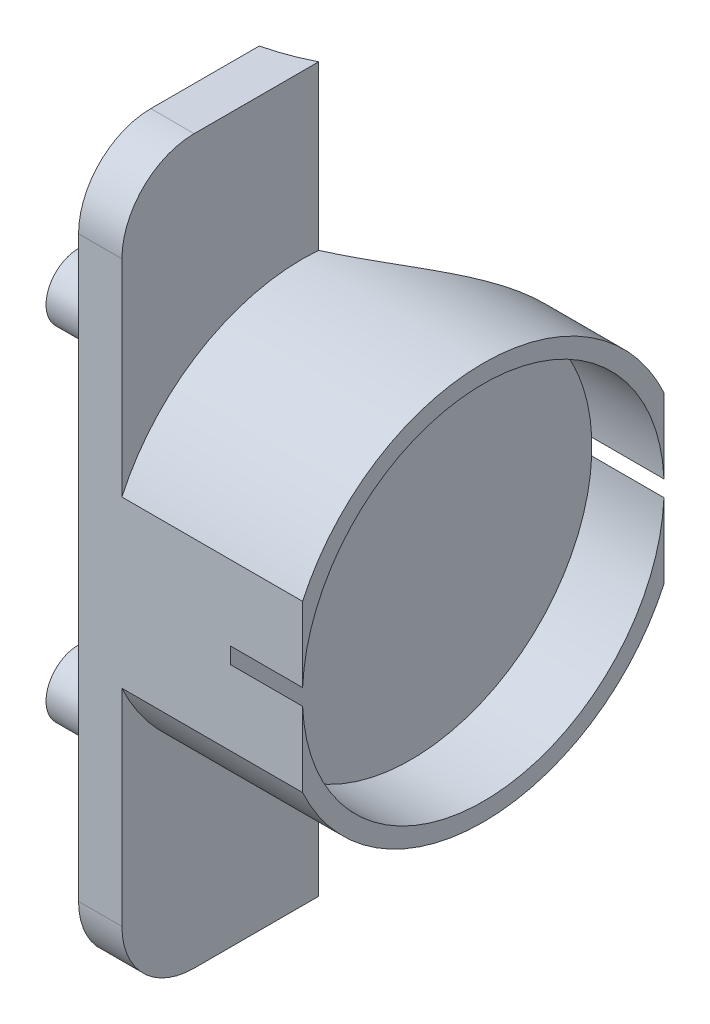
SolidWorks part; units mm, degrees
ref_plane "Front Plane" through (0, 0, 0) normal (1, 0, 0) x (0, 1, 0)
ref_plane "Top Plane" through (0, 0, 0) normal (0, 0, 1) x (0, 1, 0)
ref_plane "Right Plane" through (0, 0, 0) normal (0, 1, 0) x (-1, 0, 0)
sketch "Sketch1" plane through (0, 0, 0) normal (1, 0, 0) x (0, 1, 0)
  line L1 (-10, 5) -> (10, 5)
  line L2 (-10, 5) -> (-10, -5)
  line L3 (-10, -5) -> (10, -5)
  line L4 (10, 5) -> (10, -5)
  line L5 (-10, 5) -> (10, -5) construction
  line L6 (-10, -5) -> (10, 5) construction
  point P0 (0, 0)
  dimension "D1" = 10
  dimension "D2" = 20
extrude "Boss-Extrude1" add sketch "Sketch1" along normal blind 6.2
sketch "Sketch2" plane through (0, 0, 0) normal (1, 0, 0) x (0, 1, 0)
  line L0 (-10, 5) -> (-10, 1) construction
  line L1 (-10, 5) -> (-10, -5) construction
  line L2 (-10, 3) -> (-4.75, 3) construction
  line L4 (0, -55) -> (0, 55) construction
  circle A0 centre (-4.75, 3) radius 0.9
  circle A1 centre (4.75, 3) radius 0.9
  dimension "D3" = 1.8
  dimension "D1" = 4
  dimension "D2" = 5.25
extrude "Boss-Extrude2" add sketch "Sketch2" against normal blind 2
fillet "Fillet1" radius 2 2 edges at (3.1, 10, 5) (3.1, -10, 5)
sketch "Sketch3" plane through (6.2, 0, 0) normal (1, 0, 0) x (0, 1, 0)
  circle A0 centre (0, 0) radius 5.005
  dimension "D1" = 10.01
extrude "Cut-Extrude1" cut sketch "Sketch3" against normal blind 2 and the other way through all
sketch "Sketch4" plane through (0, 0, 0) normal (0, 1, 0) x (-1, 0, 0)
  line L0 (-6.2, -5) -> (-4.2, -5) construction
  line L1 (-6.2, -5) -> (0, -5) construction
  line L4 (-4.2, -5) -> (0, -5)
  line L6 (0, 0) -> (0, -5)
  arc A2 (-4.2, -5) -> (0, 0) centre (1.2891, -5.3468) cw
  dimension "D2" = 5.5
  dimension "D1" = 2
extrude "Cut-Extrude2" cut sketch "Sketch4" against normal through all both and the other way through all
sketch "Sketch5" plane through (6.2, 0, 0) normal (1, 0, 0) x (0, 1, 0)
  line L1 (0.2237, -5) -> (10, -5) construction
  line L2 (-10, 5) -> (-2.2913, 5)
  line L3 (-10, 5) -> (-10, -5)
  line L4 (-10, -5) -> (-2.2913, -5)
  line L5 (10, 5) -> (10, -5)
  line L6 (-10, 5) -> (10, -5) construction
  line L7 (-10, -5) -> (10, 5) construction
  line L8 (2.2913, -5) -> (10, -5)
  line L9 (2.2913, 5) -> (10, 5)
  arc A0 (-2.2913, 5) -> (-2.2913, -5) centre (0, 0) ccw
  arc A1 (2.2913, -5) -> (2.2913, 5) centre (0, 0) ccw
  dimension "D1" = 11
extrude "Cut-Extrude3" cut sketch "Sketch5" against normal blind 5
